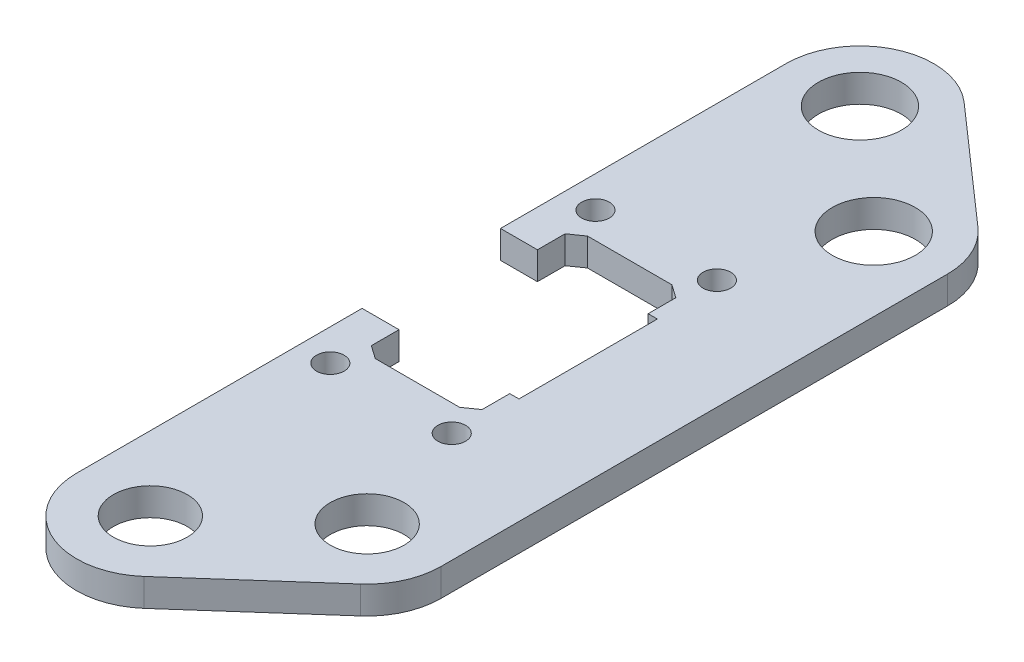
SolidWorks part; units mm, degrees
material "Chipboard"
ref_plane "Front Plane" through (0, 0, 0) normal (0, 0, 1) x (1, 0, 0)
ref_plane "Top Plane" through (0, 0, 0) normal (0, 1, 0) x (1, 0, 0)
ref_plane "Right Plane" through (0, 0, 0) normal (1, 0, 0) x (0, 0, -1)
sketch "Sketch1" plane through (0, 0, 0) normal (0, 1, 0) x (1, 0, 0)
  line L0 (-10, 0) -> (15, 0)
  line L1 (-10, -7.5) -> (-6, -7.5)
  line L2 (-6, -10.5) -> (-6, 0)
  line L3 (-3.1437, -12.5) -> (3.1437, -12.5) construction
  line L4 (6, 7.5) -> (7, 7.5)
  line L5 (-6, -10.5) -> (6, -10.5) construction
  line L6 (-4.5719, -11.5) -> (4.5719, -11.5)
  line L7 (6, -10.5) -> (6, 0)
  line L8 (6, -7.5) -> (7, -7.5)
  line L9 (8.4264, -11.2425) -> (3.516, -14.6808) construction
  line L10 (-9.4264, -10.5423) -> (-3.516, -14.6808) construction
  line L11 (6, -10.5) -> (4.5719, -11.5)
  line L12 (4.5719, -11.5) -> (10.0942, -19.3867) construction
  line L13 (-6, -10.5) -> (-4.5719, -11.5)
  line L14 (7, -7.5) -> (7, 7.5)
  line L15 (0, -40) -> (0, 0) construction
  line L16 (-4.5719, -11.5) -> (-8.574, -17.2157) construction
  line L20 (-6, 10.5) -> (-4.5719, 11.5)
  line L22 (-10, -40) -> (-10, 40)
  line L24 (6, 10.5) -> (4.5719, 11.5)
  line L25 (-10, 8.75) -> (-10, -8.75)
  line L26 (9, -12.0617) -> (4.0896, -15.5) construction
  line L27 (-2, 38.45) -> (-2, -38.45) construction
  line L28 (-4.5719, 11.5) -> (4.5719, 11.5)
  line L29 (-6, 10.5) -> (6, 10.5) construction
  line L30 (10.5, 27.45) -> (10.5, -27.45) construction
  line L31 (-3.1437, 12.5) -> (3.1437, 12.5) construction
  line L32 (-6, 10.5) -> (-6, 0)
  line L33 (-10, 7.5) -> (-6, 7.5)
  line L34 (6, 10.5) -> (6, 0)
  line L37 (-4.0896, -15.5) -> (4.0896, -15.5) construction
  line L38 (-10, -11.3615) -> (-4.0896, -15.5) construction
  line L39 (9, -12.0617) -> (9, 12.0617) construction
  line L41 (9, 12.0617) -> (4.0896, 15.5) construction
  line L42 (-4.0896, 15.5) -> (4.0896, 15.5) construction
  line L43 (-10, 11.3615) -> (-4.0896, 15.5) construction
  line L72 (-2, 0) -> (10.5, 0) construction
  line L76 (18.5, -27.45) -> (18.5, 27.45)
  line L77 (15.7968, -33.4454) -> (3.3367, -44.4791)
  line L78 (-10, 38.45) -> (-10, 8.75)
  line L79 (-10, -38.4494) -> (-10, -8.75)
  line L81 (15.785, 33.4557) -> (3.285, 44.4557)
  circle A0 centre (6.5794, -14.367) radius 1.5
  circle A1 centre (-6.5794, -14.367) radius 1.5
  circle A2 centre (-6.5794, 14.367) radius 1.5
  circle A3 centre (6.5794, 14.367) radius 1.5
  arc A24 (-10, 38.45) -> (3.285, 44.4557) centre (-2, 38.45) cw
  circle A27 centre (10.5, 27.45) radius 4.5
  arc A28 (15.7968, -33.4454) -> (18.5, -27.45) centre (10.5, -27.45) ccw
  circle A29 centre (-2, 38.45) radius 4.5
  arc A30 (15.785, 33.4557) -> (18.5, 27.45) centre (10.5, 27.45) cw
  circle A31 centre (-2, -38.45) radius 4.5
  circle A32 centre (10.5, -27.45) radius 4.5
  arc A33 (-10, -38.4494) -> (3.3367, -44.4791) centre (-1.9689, -38.45) ccw
  point P1 (-4.5, -7.5)
  point P2 (18.5, -7.5)
  point P3 (-1.5, -40)
  point P4 (-1.5, 40)
  point P5 (10.5, -12.5)
  point P14 (-4.5, -12.5)
  point P15 (18.5, -12.5)
  point P18 (-4.5, -10.5)
  point P21 (18.5, -10.5)
  point P24 (-4.5, -11.5)
  point P25 (18.5, -11.5)
  point P26 (-1.5, -12.5)
  point P29 (11.5, -12.5)
  point P36 (11.5, 0)
  point P44 (10.5, 0)
  point P48 (-1.5, 0)
  dimension "D4" = 3
  dimension "D2" = 4
  dimension "D3" = 6
  dimension "D5" = 3
  dimension "D9" = 3
  dimension "D10" = 1
  dimension "D11" = 6
  dimension "D12" = 6
  dimension "D20" = 35
  dimension "D31" = 1
  dimension "D36" = 54.9
  dimension "D37" = 76.9
  dimension "D41" = 3.5
  dimension "D42" = 3.5
  dimension "D46" = 12.5
  dimension "D38" = 9
  dimension "D39" = 3.5
  dimension "D40" = 9
  dimension "D43" = 3.5
  dimension "D6" = 6
  dimension "D7" = 10.5
  dimension "D8" = 3
  dimension "D13" = 12.5
  dimension "D14" = 7.5
  dimension "D15" = 10.5
  dimension "D16" = 35
  dimension "D17" = 35
  dimension "D18" = 11.5
  dimension "D19" = 12.5
  dimension "D21" = 35
  dimension "D22" = 3
  dimension "D23" = 3
  dimension "D24" = 3
  dimension "D32" = 1
  dimension "D33" = 11.5
  dimension "D25" = 1
  dimension "D26" = 1
extrude "Boss-Extrude1" add sketch "Sketch1" along normal blind 3
sketch "Sketch2" plane through (0, 3, 0) normal (0, 1, 0) x (1, 0, 0)
  line L0 (-7, -7.5) -> (-7, -15.8068)
  line L1 (2.0589, -16.5) -> (0.4651, -16.5)
  line L2 (-7, -19.8364) -> (-7, -22.6079)
  line L3 (6.5794, -14.367) -> (10.5, -27.45) construction
  line L4 (-7, -7.5) -> (-7, -38.4494) construction
  line L5 (4.5719, -16.5) -> (-4.5719, -16.5) construction
  line L6 (5.9868, -19.3569) -> (6.1484, -19.896)
  line L7 (9.6524, -17.6544) -> (10.1923, -19.4559)
  line L8 (10.5, -27.45) -> (-1.9689, -38.45) construction
  line L9 (4.6635, -14.9412) -> (8.5842, -28.0241) construction
  line L10 (8.4952, -13.7929) -> (12.4158, -26.8759) construction
  line L11 (3.3682, -31.0746) -> (2.5407, -31.8046)
  line L12 (-7, -24.6079) -> (10.5, -24.6079) construction
  line L13 (9.1769, -25.9502) -> (-3.292, -36.9502) construction
  line L14 (10.5, -27.45) -> (10.5, 27.45) construction
  line L15 (-1.5349, -16.5) -> (-1.5349, -40.0867) construction
  line L16 (-6, -25.6079) -> (-2.5349, -25.6079)
  line L17 (-2.5349, -18.9476) -> (-2.5349, -23.6079)
  line L18 (-6, -23.6079) -> (-2.5349, -23.6079)
  line L19 (-0.5349, -17.5) -> (-0.5349, -23.6079)
  line L20 (-10, -7.5) -> (-10, -38.4494)
  line L21 (3.3367, -44.4791) -> (15.7968, -33.4454)
  line L22 (18.5, -27.45) -> (18.5, 27.45)
  line L23 (15.785, 33.4557) -> (3.285, 44.4557)
  line L24 (-10, 38.45) -> (-10, 7.5)
  line L25 (-10, 7.5) -> (-6, 7.5)
  line L26 (-6, 7.5) -> (-6, 10.5)
  line L27 (-6, 10.5) -> (-4.5719, 11.5)
  line L28 (-4.5719, 11.5) -> (4.5719, 11.5)
  line L29 (4.5719, 11.5) -> (6, 10.5)
  line L30 (6, 10.5) -> (6, 7.5)
  line L31 (6, 7.5) -> (7, 7.5)
  line L32 (7, 7.5) -> (7, -7.5)
  line L33 (7, -7.5) -> (6, -7.5)
  line L34 (6, -7.5) -> (6, -10.5)
  line L35 (6, -10.5) -> (4.5719, -11.5)
  line L36 (4.5719, -11.5) -> (-4.5719, -11.5)
  line L37 (-4.5719, -11.5) -> (-6, -10.5)
  line L38 (-6, -10.5) -> (-6, -7.5)
  line L39 (-6, -7.5) -> (-10, -7.5)
  line L40 (-10, -7.5) -> (-10, -38.4494)
  line L41 (3.3367, -44.4791) -> (15.7968, -33.4454)
  line L42 (18.5, -27.45) -> (18.5, 27.45)
  line L43 (15.785, 33.4557) -> (3.285, 44.4557)
  line L44 (-10, 38.45) -> (-10, 7.5)
  line L45 (-10, 7.5) -> (-6, 7.5)
  line L46 (-6, 7.5) -> (-6, 10.5)
  line L47 (-6, 10.5) -> (-4.5719, 11.5)
  line L48 (-4.5719, 11.5) -> (4.5719, 11.5)
  line L49 (4.5719, 11.5) -> (6, 10.5)
  line L50 (6, 10.5) -> (6, 7.5)
  line L51 (6, 7.5) -> (7, 7.5)
  line L52 (7, 7.5) -> (7, -7.5)
  line L53 (7, -7.5) -> (6, -7.5)
  line L54 (6, -7.5) -> (6, -10.5)
  line L55 (6, -10.5) -> (4.5719, -11.5)
  line L56 (4.5719, -11.5) -> (-4.5719, -11.5)
  line L57 (-4.5719, -11.5) -> (-6, -10.5)
  line L58 (-6, -10.5) -> (-6, -7.5)
  line L59 (-6, -7.5) -> (-10, -7.5)
  line L60 (-0.5349, -16.5185) -> (-0.5349, -40.0867) construction
  line L61 (-1.5349, -16.5185) -> (-1.5349, -40.0867) construction
  line L62 (-2.5349, -16.5185) -> (-2.5349, -40.0867) construction
  line L63 (-2.5349, -16.5) -> (-2.617, -16.5)
  line L64 (-7, -26.6079) -> (-7, -30.3685)
  line L65 (-7, -25.6079) -> (10.5, -25.6079) construction
  line L66 (-7, -23.6079) -> (10.5, -23.6079) construction
  line L67 (-0.5349, -25.6079) -> (-0.5349, -29.7531)
  line L68 (-0.5349, -23.6079) -> (2.9136, -23.6079)
  line L69 (-2.5349, -25.6079) -> (-2.5349, -29.5557)
  line L70 (-0.5349, -25.6079) -> (1.5395, -25.6079)
  circle A0 centre (-2, -38.45) radius 4.5 construction
  circle A1 centre (-2, -38.45) radius 4.5
  circle A2 centre (-6.5794, -14.367) radius 1.5 construction
  circle A3 centre (-6.5794, -14.367) radius 1.5
  arc A4 (-10, -38.4494) -> (3.3367, -44.4791) centre (-1.9689, -38.45) ccw
  arc A5 (15.7968, -33.4454) -> (18.5, -27.45) centre (10.5, -27.45) ccw
  arc A6 (18.5, 27.45) -> (15.785, 33.4557) centre (10.5, 27.45) ccw
  arc A7 (3.285, 44.4557) -> (-10, 38.45) centre (-2, 38.45) ccw
  arc A8 (-10, -38.4494) -> (3.374, -44.446) centre (-1.9689, -38.45) ccw
  arc A9 (15.7968, -33.4454) -> (18.5, -27.45) centre (10.5, -27.45) ccw
  arc A10 (18.5, 27.45) -> (15.785, 33.4557) centre (10.5, 27.45) ccw
  arc A11 (3.285, 44.4557) -> (-10, 38.45) centre (-2, 38.45) ccw
  circle A12 centre (6.5794, -14.367) radius 1.5 construction
  circle A13 centre (6.5794, -14.367) radius 1.5
  circle A14 centre (10.5, -27.45) radius 4.5 construction
  circle A15 centre (10.5, -27.45) radius 4.5
  circle A16 centre (6.5794, 14.367) radius 1.5 construction
  circle A17 centre (6.5794, 14.367) radius 1.5
  circle A18 centre (-6.5794, 14.367) radius 1.5 construction
  circle A19 centre (-6.5794, 14.367) radius 1.5
  circle A20 centre (-2, 38.45) radius 4.5 construction
  circle A21 centre (-2, 38.45) radius 4.5
  arc A22 (-5.5536, -31.2633) -> (-3.3615, -30.5406) centre (-1.9689, -38.45) cw
  arc A23 (5.7804, -20.9905) -> (3.7565, -23.1459) centre (10.5, -27.45) ccw
  arc A24 (-6.1053, -18.842) -> (-4.0885, -18.1148) centre (-6.5794, -14.367) ccw
  arc A25 (9.6524, -17.6544) -> (3.1109, -11.5) centre (6.5794, -14.367) ccw
  arc A26 (2.8808, -16.9304) -> (5.3108, -18.6845) centre (6.5794, -14.367) ccw
  circle A27 centre (-6.5794, -14.367) radius 4.5 construction
  circle A28 centre (6.5794, -14.367) radius 4.5 construction
  arc A29 (-5.5536, -31.2633) -> (-7, -30.3685) centre (-6, -30.3685) cw
  arc A30 (0.1956, -30.7161) -> (1.5348, -31.2235) centre (-1.9689, -38.45) cw
  arc A31 (2.5351, -26.7015) -> (2.9188, -30.0044) centre (10.5, -27.45) ccw
  arc A32 (-3.3615, -30.5406) -> (-2.5349, -29.5557) centre (-3.5349, -29.5557) ccw
  arc A33 (-7, -26.6079) -> (-6, -25.6079) centre (-6, -26.6079) cw
  arc A34 (-7, -22.6079) -> (-6, -23.6079) centre (-6, -22.6079) ccw
  arc A35 (-6.1053, -18.842) -> (-7, -19.8364) centre (-6, -19.8364) ccw
  arc A36 (-2.5349, -18.9476) -> (-4.0885, -18.1148) centre (-3.5349, -18.9476) ccw
  arc A37 (0.4651, -16.5) -> (-0.5349, -17.5) centre (0.4651, -17.5) ccw
  arc A38 (2.8808, -16.9304) -> (2.0589, -16.5) centre (2.0589, -17.5) ccw
  arc A39 (5.9868, -19.3569) -> (5.3108, -18.6845) centre (5.0289, -19.644) ccw
  arc A40 (5.7804, -20.9905) -> (6.1484, -19.896) centre (5.1905, -20.183) ccw
  arc A41 (2.9136, -23.6079) -> (3.7565, -23.1459) centre (2.9136, -22.6079) ccw
  arc A42 (2.5351, -26.7015) -> (1.5395, -25.6079) centre (1.5395, -26.6079) ccw
  arc A43 (1.5348, -31.2235) -> (2.9188, -30.0044) centre (1.9711, -30.3237) ccw
  arc A44 (2.5407, -31.8046) -> (4.0536, -33.137) centre (-1.9689, -38.45) cw
  arc A45 (3.3682, -31.0746) -> (4.5008, -32.7424) centre (10.5, -27.45) ccw
  arc A46 (-0.5349, -29.7531) -> (0.1956, -30.7161) centre (0.4651, -29.7531) ccw
  arc A47 (7.0202, -34.6536) -> (5.6381, -35.8747) centre (6.5853, -35.554) ccw
  arc A48 (5.6381, -35.8747) -> (3.3367, -44.4791) centre (-1.9689, -38.45) cw
  arc A49 (7.0202, -34.6536) -> (15.7968, -33.4454) centre (10.5, -27.45) ccw
  point P48 (-2.0794, -14.367)
  point P69 (11.0794, -14.367)
  point P115 (2.617, -16.5)
  dimension "D8" = 1
  dimension "D11" = 1
  dimension "D12" = 1
  dimension "D13" = 1
  dimension "D14" = 1
  dimension "D15" = 1
  dimension "D16" = 1
  dimension "D17" = 1
  dimension "D18" = 1
  dimension "D19" = 1
  dimension "D20" = 1
  dimension "D21" = 1
  dimension "D22" = 1
  dimension "D1" = 0
  dimension "D2" = 3
  dimension "D3" = 3
  dimension "D4" = 5
  dimension "D5" = 2
  dimension "D6" = 2
  dimension "D7" = 2
  dimension "D9" = 1
  dimension "D10" = 1
extrude "Cut-Extrude1" [suppressed] cut sketch "Sketch2" against normal blind 3 contours A49 A47 A48 L41 | L67 A46 A30 A43 A31 A42 L70 | A33 L64 A29 A22 A32 L69 L16 | L17 A36 A24 A35 L2 A34 L18 | L68 A41 A23 A40 L6 A39 A26 A38 L1 A37 L19
sketch "Sketch3" plane through (0, 3, 0) normal (0, 1, 0) x (1, 0, 0)
  circle A0 centre (-2, -38.45) radius 4.5 construction
  circle A1 centre (-2, -38.45) radius 4.5
  circle A2 centre (10.5, -27.45) radius 4.5 construction
  circle A3 centre (10.5, -27.45) radius 4.5
  circle A4 centre (-2, -38.45) radius 4
  circle A5 centre (10.5, -27.45) radius 4
  dimension "D1" = 0.5
extrude "Boss-Extrude2" add sketch "Sketch3" against normal up to surface (3 mm away) up to face at (-2, 0, -33.95)
mirror "Mirror1" [suppressed] about plane through (0, 0, 0) normal (0, 0, 1)
sketch "Sketch4" [suppressed] plane through (0, 3, 0) normal (0, 1, 0) x (1, 0, 0)
  line L0 (11.0794, -14.367) -> (11.0794, 14.367)
  line L1 (18.5, -27.45) -> (18.5, 27.45) construction
  line L2 (18.5, -27.45) -> (18.5, 27.45)
  circle A0 centre (10.5, -27.45) radius 4 construction
  circle A1 centre (10.5, -27.45) radius 4
  circle A2 centre (10.5, 27.45) radius 4 construction
  circle A3 centre (10.5, 27.45) radius 4
  circle A4 centre (10.5, -27.45) radius 8
  circle A5 centre (10.5, 27.45) radius 8
  circle A6 centre (6.5794, -14.367) radius 1.5 construction
  circle A7 centre (6.5794, -14.367) radius 1.5
  circle A8 centre (6.5794, 14.367) radius 1.5 construction
  circle A9 centre (6.5794, 14.367) radius 1.5
  arc A10 (9.5915, -17.7102) -> (11.0794, -14.367) centre (6.5794, -14.367) ccw
  arc A11 (11.0794, 14.367) -> (9.5915, 17.7102) centre (6.5794, 14.367) ccw
  arc A12 (9.5915, -17.7102) -> (10.2874, -19.4528) centre (10.2609, -18.4532) ccw
  arc A13 (7.0202, -34.6536) -> (18.5, -27.45) centre (10.5, -27.45) ccw construction
  arc A14 (10.2874, 19.4528) -> (9.5915, 17.7102) centre (10.2609, 18.4532) ccw
  circle A15 centre (6.5794, -14.367) radius 4.5 construction
  arc A16 (18.5, 27.45) -> (7.0202, 34.6536) centre (10.5, 27.45) ccw construction
  circle A18 centre (6.5794, 14.367) radius 4.5 construction
  point P21 (11.0794, -14.367)
  point P28 (11.0794, 14.367)
  dimension "D1" = 3
extrude "Cut-Extrude2" [suppressed] cut sketch "Sketch4" against normal blind 3 contours A5 A14 A11 L0 A10 A12 A4 L2
